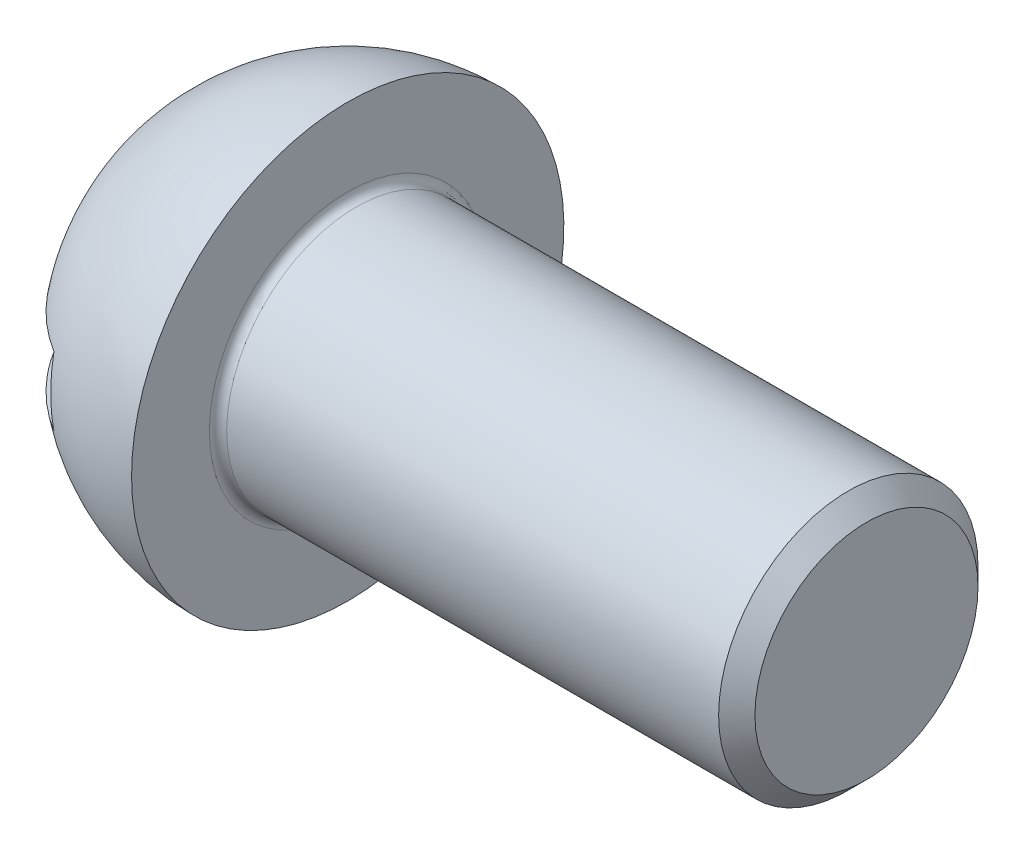
SolidWorks part; units mm, degrees
ref_plane "Přední rovina" through (0, 0, 0) normal (0, 0, 1) x (1, 0, 0)
ref_plane "Vrchní rovina" through (0, 0, 0) normal (0, 1, 0) x (1, 0, 0)
ref_plane "Pravá rovina" through (0, 0, 0) normal (1, 0, 0) x (0, 0, -1)
sketch "Skica1" plane through (0, 0, 0) normal (0, 1, 0) x (1, 0, 0)
  line L0 (0, 0) -> (8.5, 0) construction
  line L1 (2.5, 2.5) -> (2.5, 1.5)
  line L2 (2.5, 1.5) -> (8.5, 1.5)
  line L3 (8.5, 1.5) -> (8.5, 0)
  line L4 (8.5, 0) -> (0, 0)
  arc A0 (0, 0) -> (2.5, 2.5) centre (2.5, 0) cw
  dimension "R1" = 2.5
  dimension "M" = 3
  dimension "l" = 6
  dimension "k" = 2.5
revolve "Otočit kolem osy1" add sketch "Skica1" angle 360 about L0
cosmetic thread "Kosmetický závit1" parameters "b"=5.9, "D2"=2.55
chamfer "Zkosit1" distance 0.21 angle 45 1 edges at (8.5, 0, 1.5)
fillet "Zaoblit1" radius 0.1 1 edges at (2.5, 0, 1.5)
sketch "Skica3" plane through (0, 0, 0) normal (1, 0, 0) x (0, 0, -1)
  line L0 (0, 0.4) -> (0, 0) construction
  line L1 (2.5, 0.4) -> (-2.5, 0.4)
  line L2 (2.5, 0.4) -> (2.5, -0.4)
  line L3 (2.5, -0.4) -> (-2.5, -0.4)
  line L4 (-2.5, 0.4) -> (-2.5, -0.4)
  line L5 (0, 0) -> (-2.5, 0) construction
  circle A0 centre (0, 0) radius 2.5 construction
  dimension "n" = 0.8
extrude "Odebrat vysunutím2" cut sketch "Skica3" along normal blind 1.2
equation "\"D1@Zkosit1\" = 0.07 * \"M@Skica1\""
equation "\"D2@Kosmetický závit1\" = 0.85 * \"M@Skica1\""
